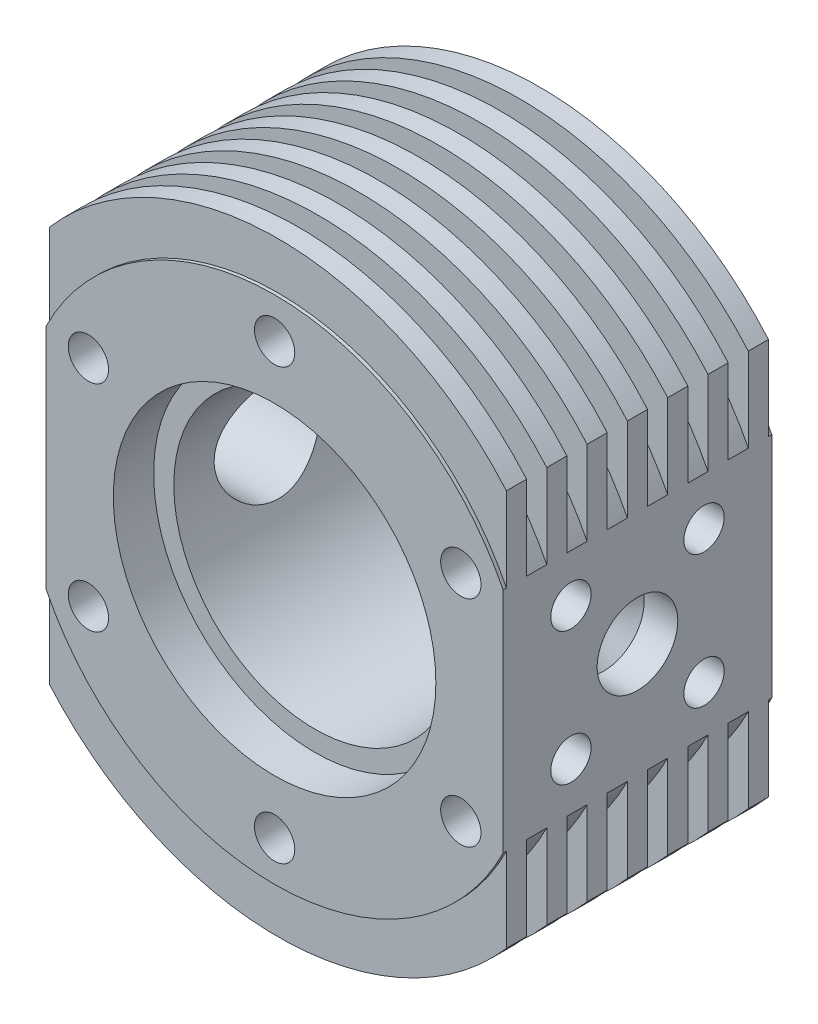
SolidWorks part; units mm, degrees
ref_plane "Front Plane" through (0, 0, 0) normal (0, 0, 1) x (1, 0, 0)
ref_plane "Top Plane" through (0, 0, 0) normal (0, 1, 0) x (1, 0, 0)
ref_plane "Right Plane" through (0, 0, 0) normal (1, 0, 0) x (0, 0, -1)
sketch "Sketch1" plane through (0, 0, 0) normal (0, 0, 1) x (1, 0, 0)
  line L2 (-17, -14.7394) -> (-17, 14.7394)
  line L4 (17, -14.7394) -> (17, 14.7394)
  line L5 (-11.5775, -19.2928) -> (11.5775, 19.2928) construction
  line L6 (-11.5775, 19.2928) -> (11.5775, -19.2928) construction
  arc A0 (-17, -14.7394) -> (17, -14.7394) centre (0, 0) ccw
  circle A1 centre (0, 0) radius 10.5
  arc A2 (17, 14.7394) -> (-17, 14.7394) centre (0, 0) ccw
  dimension "D1" = 45
  dimension "D2" = 21
  dimension "D3" = 34
  dimension "D4" = 29.4788
extrude "Boss-Extrude1" add sketch "Sketch1" along normal blind 20
sketch "Sketch2" plane through (0, 0, 20) normal (0, 0, 1) x (1, 0, 0)
  circle A0 centre (0, 0) radius 12
  dimension "D1" = 24
extrude "Cut-Extrude1" cut sketch "Sketch2" against normal blind 3
sketch "Sketch3" plane through (0, 0, 0) normal (0, 0, 1) x (1, 0, 0)
  circle A0 centre (0, 0) radius 19
  dimension "D1" = 38
extrude "Cut-Extrude2" cut sketch "Sketch3" along normal blind 0.25 flip side to cut
sketch "Sketch4" plane through (0, 0, 20) normal (0, 0, 1) x (1, 0, 0)
  circle A0 centre (0, 0) radius 19
  dimension "D1" = 38
extrude "Cut-Extrude3" cut sketch "Sketch4" against normal blind 0.25 flip side to cut
ref_plane "Plane1" through (0, 0, 18.25) normal (0, 0, 1) x (1, 0, 0)
sketch "Sketch5" plane through (0, 0, 18.25) normal (0, 0, 1) x (1, 0, 0)
  line L0 (-17, -8.4853) -> (-17, -14.7394) construction
  line L1 (17, -14.7394) -> (17, -8.4853) construction
  line L2 (-17, -8.4853) -> (-17, -14.7394)
  line L3 (17, -14.7394) -> (17, -8.4853)
  arc A0 (-17, -8.4853) -> (17, -8.4853) centre (0, 0) ccw construction
  arc A1 (-17, -14.7394) -> (17, -14.7394) centre (0, 0) ccw construction
  arc A2 (-17, -8.4853) -> (17, -8.4853) centre (0, 0) ccw
  arc A3 (-17, -14.7394) -> (17, -14.7394) centre (0, 0) ccw
extrude "Cut-Extrude4" cut sketch "Sketch5" against normal blind 1.5
pattern_linear "LPattern1" count 6 spacing 3 along (0, 0, -1) of "Cut-Extrude4"
mirror "Mirror1" about plane through (0, 0, 0) normal (0, 1, 0) of "LPattern1", "Cut-Extrude4"
sketch "Sketch6" plane through (-17, 0, 0) normal (-1, 0, 0) x (0, 0, 1)
  circle A0 centre (10, 0) radius 4
  dimension "D1" = 8
  dimension "D2" = 10
extrude "Cut-Extrude5" cut sketch "Sketch6" against normal up to next
sketch "Sketch7" plane through (-17, 0, 0) normal (-1, 0, 0) x (0, 0, 1)
  line L0 (10, 7) -> (10, 0) construction
  line L1 (10, 0) -> (14.9497, 4.9497) construction
  circle A0 centre (10, 0) radius 7 construction
  circle A1 centre (14.9497, 4.9497) radius 1.5
  circle A2 centre (14.9497, -4.9497) radius 1.5
  circle A3 centre (5.0503, -4.9497) radius 1.5
  circle A4 centre (5.0503, 4.9497) radius 1.5
  point P15 (10, 0)
  dimension "D1" = 14
  dimension "D3" = 3
  dimension "D2" = 45
  dimension "D4" = 4
extrude "Cut-Extrude6" cut sketch "Sketch7" against normal blind 4
ref_plane "Plane2" through (0, 0, 10) normal (0, 0, -1) x (-1, 0, 0)
sketch "Sketch8" plane through (0, 0, 10) normal (0, 0, -1) x (-1, 0, 0)
  line L0 (-17, 0) -> (-11.5, 0)
  line L1 (-17, -8.4853) -> (-17, 8.4853) construction
  line L2 (-11.5, 0) -> (-14.5, -3)
  line L3 (-14.5, -3) -> (-17, -3)
  line L4 (-17, -3) -> (-17, 0)
  dimension "D1" = 3
  dimension "D2" = 45
  dimension "D3" = 2.5
revolve "Cut-Revolve1" cut sketch "Sketch8" angle 360 about L0
mirror "Mirror2" about plane through (0, 0, 0) normal (1, 0, 0) of "Cut-Extrude6"
sketch "Sketch9" plane through (0, 0, 20) normal (0, 0, 1) x (1, 0, 0)
  circle A0 centre (0, 0) radius 16 construction
  circle A1 centre (0, 16) radius 1.5
  circle A2 centre (13.8564, 8) radius 1.5
  circle A3 centre (13.8564, -8) radius 1.5
  circle A4 centre (0, -16) radius 1.5
  circle A5 centre (-13.8564, -8) radius 1.5
  circle A6 centre (-13.8564, 8) radius 1.5
  point P17 (0, 0)
  dimension "D1" = 32
  dimension "D2" = 3
  dimension "D3" = 6
extrude "Cut-Extrude7" cut sketch "Sketch9" against normal blind 6
mirror "Mirror3" about plane through (0, 0, 10) normal (0, 0, -1) of "Cut-Extrude7"
